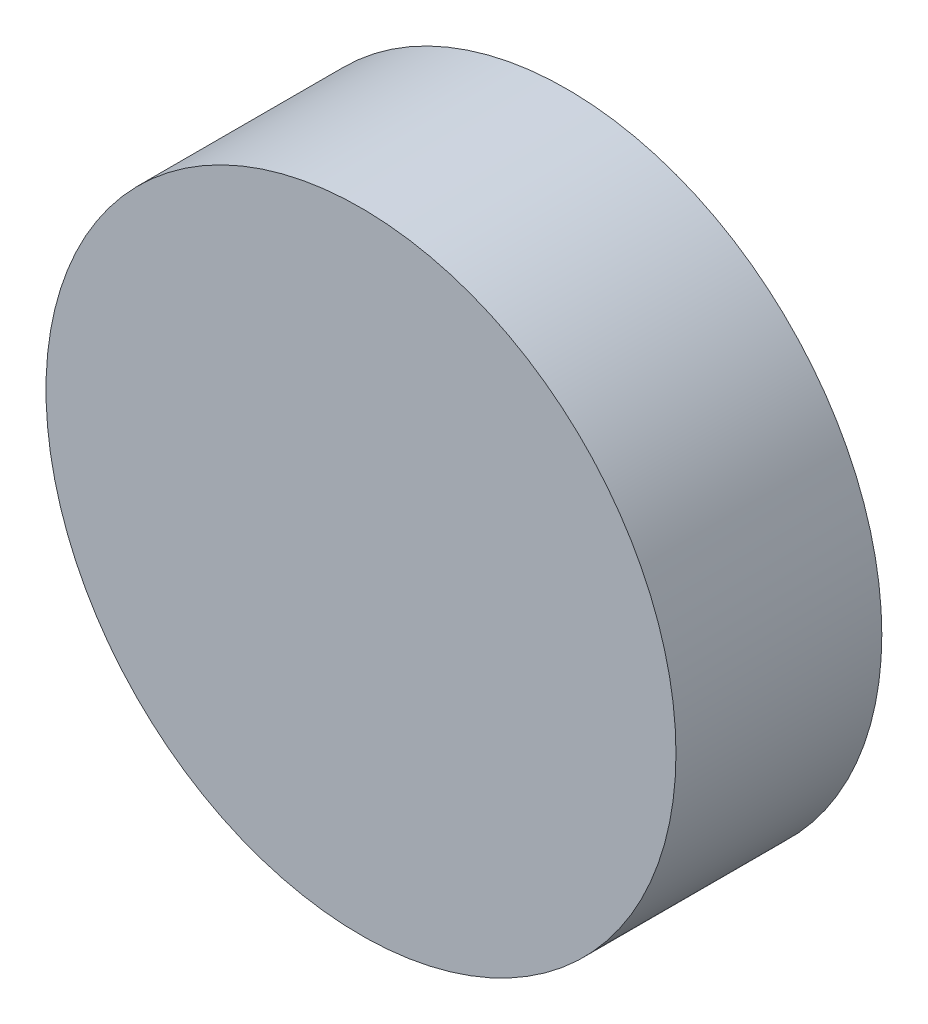
SolidWorks part; units mm, degrees
ref_plane "정면" through (0, 0, 0) normal (0, 0, 1) x (1, 0, 0)
ref_plane "윗면" through (0, 0, 0) normal (0, 1, 0) x (1, 0, 0)
ref_plane "우측면" through (0, 0, 0) normal (1, 0, 0) x (0, 0, -1)
sketch "스케치1" plane through (0, 0, 0) normal (0, 0, 1) x (1, 0, 0)
  circle A0 centre (0, 0) radius 81.1
  circle A1 centre (0, 0) radius 78.1
  point P2 (0, 0)
  dimension "D1" = 3
  dimension "D2" = 162.2
extrude "보스-돌출1" add sketch "스케치1" along normal blind 50
sketch "스케치2" plane through (0, 0, 50) normal (0, 0, 1) x (1, 0, 0)
  circle A0 centre (0, 0) radius 81.1
  circle A1 centre (0, 0) radius 81.1 construction
extrude "보스-돌출2" add sketch "스케치2" along normal blind 3
sketch "스케치3" plane through (0, 0, 0) normal (0, 0, -1) x (-1, 0, 0)
  circle A1 centre (0, 0) radius 81.1
  circle A2 centre (0, 0) radius 81.1
  dimension "D1" = 0
